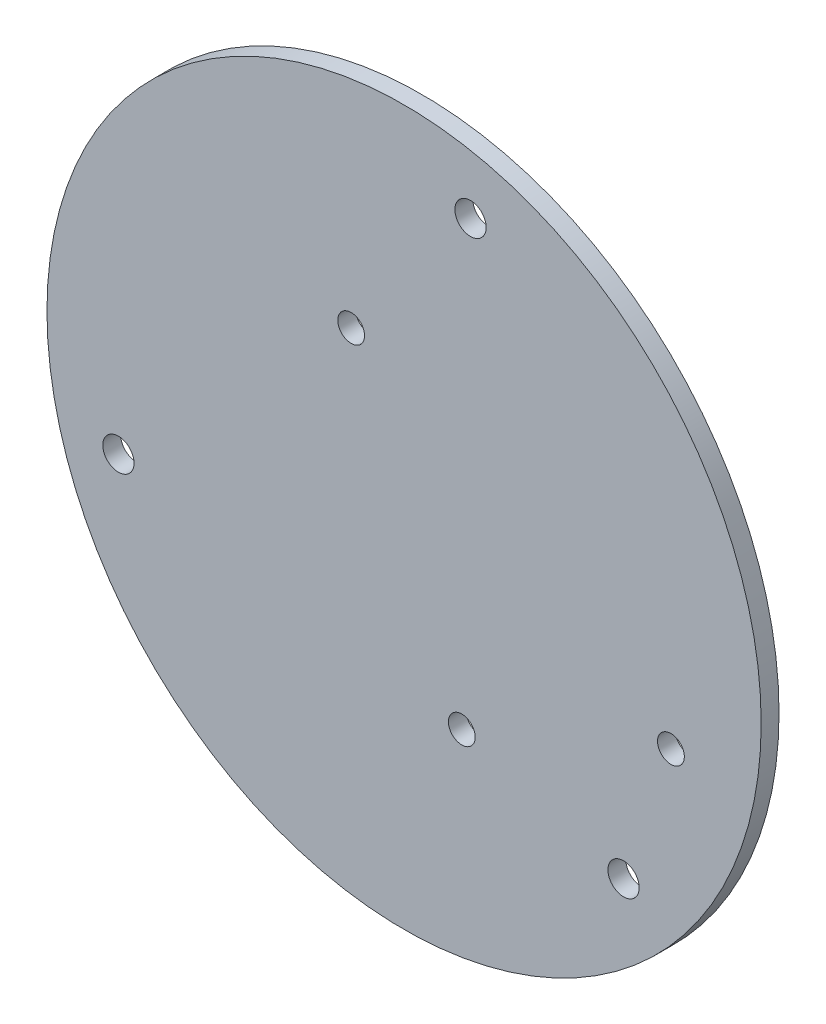
SolidWorks part; units mm, degrees
ref_plane "Front Plane" through (0, 0, 0) normal (0, 0, 1) x (1, 0, 0)
ref_plane "Top Plane" through (0, 0, 0) normal (0, 1, 0) x (1, 0, 0)
ref_plane "Right Plane" through (0, 0, 0) normal (1, 0, 0) x (0, 0, -1)
sketch "Sketch1" plane through (0, 0, 0) normal (0, 0, 1) x (1, 0, 0)
  line L0 (0, 0) -> (-31.9955, -9.8877) construction
  line L1 (7.4443, 32.6948) -> (0, 0) construction
  line L2 (0, 0) -> (24.5822, -22.7849) construction
  circle A0 centre (0, 0) radius 40
  circle A1 centre (-31.9955, -9.8877) radius 1.75
  circle A2 centre (24.5822, -22.7849) radius 1.75
  circle A3 centre (7.4443, 32.6948) radius 1.75
  circle A4 centre (-5.9247, 15.3899) radius 1.5 construction
  circle A5 centre (29.8903, -7.5401) radius 1.5 construction
  circle A6 centre (6.4659, -17.3619) radius 1.5 construction
  circle A7 centre (-5.9247, 15.3899) radius 1.5
  circle A8 centre (29.8903, -7.5401) radius 1.5
  circle A9 centre (6.4659, -17.3619) radius 1.5
  dimension "D1" = 80
  dimension "D2" = 3.5
  dimension "D3" = 120
  dimension "D4" = 120
extrude "Boss-Extrude1" add sketch "Sketch1" along normal blind 2
